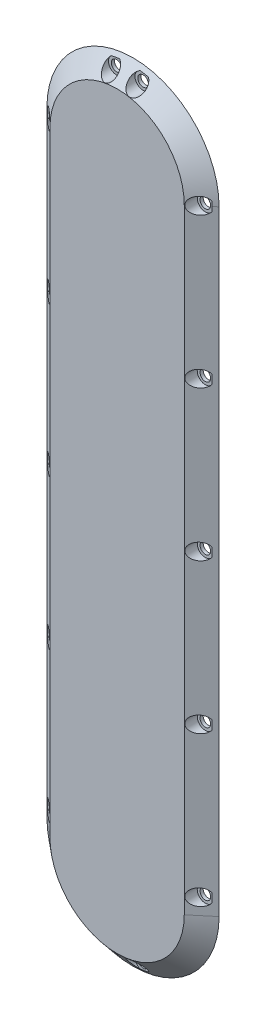
SolidWorks part; units mm, degrees
material "PVC 0.007 Plasticized"
ref_plane "Front Plane" through (0, 0, 0) normal (0, 0, 1) x (1, 0, 0)
ref_plane "Top Plane" through (0, 0, 0) normal (0, 1, 0) x (1, 0, 0)
ref_plane "Right Plane" through (0, 0, 0) normal (1, 0, 0) x (0, 0, -1)
sketch "Sketch1" plane through (0, 0, 0) normal (0, 0, 1) x (1, 0, 0)
  line L0 (0, -116) -> (0, 116) construction
  line L1 (-32.5, -116) -> (-32.5, 116)
  line L2 (32.5, -116) -> (32.5, 116)
  arc A0 (-32.5, -116) -> (32.5, -116) centre (0, -116) ccw
  arc A1 (32.5, 116) -> (-32.5, 116) centre (0, 116) ccw
  point P2 (0, 0)
  dimension "D1" = 232
  dimension "D2" = 65
extrude "Boss-Extrude1" add sketch "Sketch1" along normal blind 6 draft 50
hole_wizard "Ø1.0mm Dowel Hole2" positions "Sketch3" profile "Sketch4" hole size "Ø1.0" standard "ANSI Metric" end condition through all
sketch "Sketch3" plane through (0, 0, 6) normal (0, 0, 1) x (1, 0, 0)
  arc A0 (32.5, 116) -> (-32.5, 116) centre (0, 116) ccw construction
  point P0 (-5, 144)
  point P2 (5, 144)
  dimension "D1" = 28
  dimension "D2" = 10
  dimension "D3" = 5
sketch "Sketch4" plane through (-5, 144, 6) normal (1, 0, 0) x (0, -1, 0)
  line L0 (0, 0) -> (0, 6)
  line L1 (0, 6) -> (2, 6)
  line L2 (2, 6) -> (2, 0)
  line L5 (2, 0) -> (0, 0)
  line L11 (0, -6.35) -> (0, 107.95) construction
  dimension "Thru Hole Dia." = 4
  dimension "Thru Hole Depth" = 6
mirror "Mirror1" about plane through (0, 0, 0) normal (0, 1, 0) of "Ø1.0mm Dowel Hole2"
hole_wizard "Ø4.0mm Dowel Hole1" positions "Sketch6" profile "Sketch7" hole size "Ø4.0" standard "ANSI Metric" end condition through all
sketch "Sketch6" plane through (0, 0, 6) normal (0, 0, 1) x (1, 0, 0)
  arc A0 (25.3495, 116) -> (-25.3495, 116) centre (0, 116) ccw construction
  point P0 (28.5, 116)
  dimension "D1" = 28.5
sketch "Sketch7" plane through (28.5, 116, 6) normal (1, 0, 0) x (0, -1, 0)
  line L0 (0, 0) -> (0, 6)
  line L1 (0, 6) -> (2, 6)
  line L2 (2, 6) -> (2, 0)
  line L5 (2, 0) -> (0, 0)
  line L11 (0, -6.35) -> (0, 107.95) construction
  dimension "Thru Hole Dia." = 4
  dimension "Thru Hole Depth" = 6
pattern_linear "LPattern3" count 5 spacing 56.5 along (0, -1, 0) of "Ø4.0mm Dowel Hole1"
mirror "Mirror2" about plane through (0, 0, 0) normal (1, 0, 0) of "LPattern3", "Ø4.0mm Dowel Hole1"
sketch "Sketch8" plane through (0, 0, 6) normal (0, 0, 1) x (1, 0, 0)
  circle A0 centre (-28.5, 116) radius 3.05
  circle A1 centre (-28.5, 59.5) radius 3.05
  circle A2 centre (28.5, 59.5) radius 3.05
  circle A3 centre (28.5, 116) radius 3.05
  circle A4 centre (28.5, 3) radius 3.05
  circle A5 centre (-28.5, 3) radius 3.05
  circle A6 centre (28.5, -53.5) radius 3.05
  circle A7 centre (-28.5, -53.5) radius 3.05
  circle A8 centre (-28.5, -110) radius 3.05
  circle A9 centre (28.5, -110) radius 3.05
  circle A11 centre (5, -144) radius 3.05
  circle A12 centre (-5, -144) radius 3.05
  circle A13 centre (-5, 144) radius 3.05
  circle A14 centre (5, 144) radius 3.05
  dimension "D1" = 6.1
extrude "Cut-Extrude1" cut sketch "Sketch8" against normal blind 4.8
